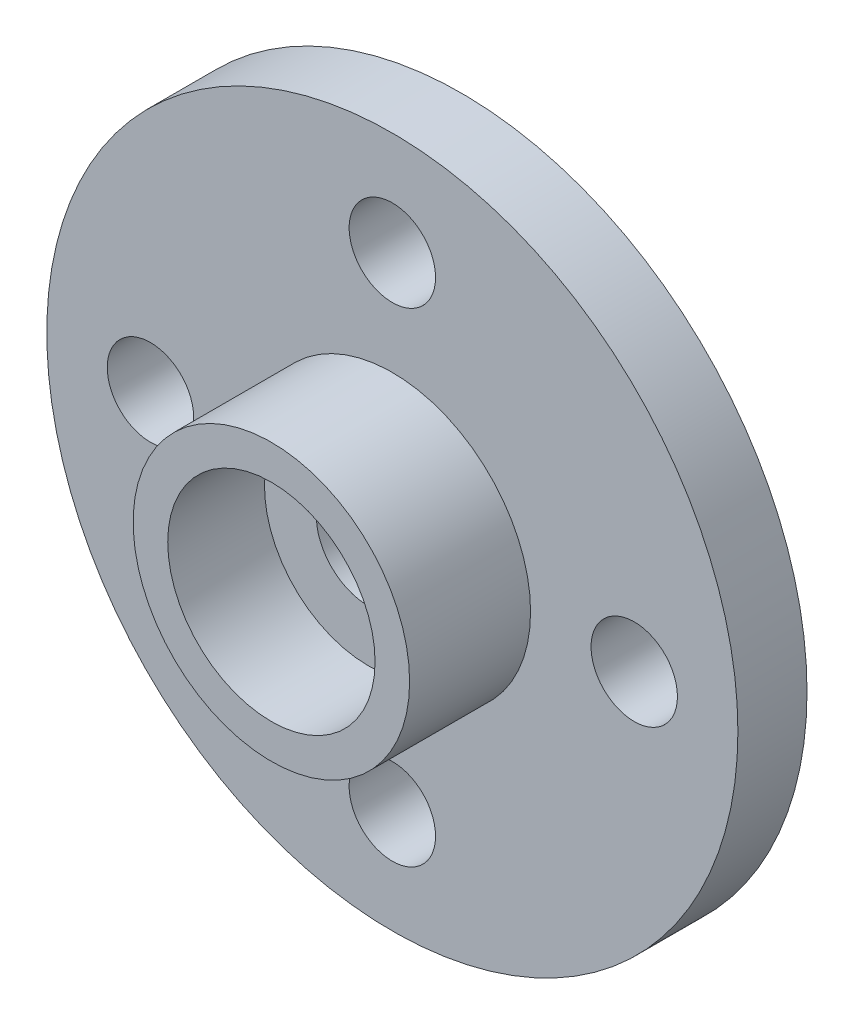
SolidWorks part; units mm, degrees
material "PF"
ref_plane "前视基准面" through (0, 0, 0) normal (0, 0, 1) x (1, 0, 0)
ref_plane "上视基准面" through (0, 0, 0) normal (0, 1, 0) x (1, 0, 0)
ref_plane "右视基准面" through (0, 0, 0) normal (1, 0, 0) x (0, 0, -1)
sketch "草图1" plane through (0, 0, 0) normal (0, 0, 1) x (1, 0, 0)
  circle A0 centre (0, 0) radius 3
  circle A1 centre (0, 0) radius 10
  dimension "D1" = 6
  dimension "D2" = 20
extrude "拉伸1" add sketch "草图1" along normal blind 2
sketch "草图2" plane through (0, 0, 2) normal (0, 0, 1) x (1, 0, 0)
  circle A0 centre (0, 0) radius 3
  circle A1 centre (0, 0) radius 4
extrude "凸台-拉伸1" add sketch "草图2" along normal blind 3.5
sketch "草图3" plane through (0, 0, 2) normal (0, 0, 1) x (1, 0, 0)
  circle A0 centre (0, 0) radius 7 construction
  point P2 (0, 7)
  point P3 (7, 0)
  point P4 (0, -7)
  point P5 (-7, 0)
  dimension "D1" = 14
hole_wizard "M3 螺纹孔1" positions "3D草图2" profile "草图5" tap size "M3" standard "GB" end condition through all
sketch3d "3D草图2"
  point P0 (-7, 0, 2)
  point P3 (0, 7, 2)
  point P6 (7, 0, 2)
  point P9 (0, -7, 2)
sketch "草图5" plane through (-7, 0, 2) normal (1, 0, 0) x (0, -1, 0)
  line L0 (0, 0) -> (0, 2)
  line L1 (0, 2) -> (1.25, 2)
  line L2 (1.25, 2) -> (1.25, 0)
  line L5 (1.25, 0) -> (0, 0)
  line L11 (0, -6.35) -> (0, 107.95) construction
  dimension "通孔螺纹孔钻头直径" = 2.5
  dimension "通孔螺纹孔钻头深度" = 2
cosmetic thread "孔螺蚊线1" parameters "D2"=3
cosmetic thread "孔螺蚊线2" parameters "D2"=3
cosmetic thread "孔螺蚊线3" parameters "D2"=3
cosmetic thread "孔螺蚊线4" parameters "D2"=3
sketch "草图6" plane through (0, 0, 0) normal (1, 0, 0) x (0, 0, -1)
  line L0 (0, 0) -> (-5.5, 0) construction
  line L2 (0, -10) -> (0, 10) construction
  line L3 (-1.4, 3) -> (-1.4, 1.5)
  line L4 (-1.4, 1.5) -> (-2.7, 1.5)
  line L5 (-2.7, 1.5) -> (-2.7, 3)
  line L6 (-2.7, 3) -> (-1.4, 3)
  line L7 (-5.5, 3) -> (-5.5, -3) construction
  dimension "D1" = 1.4
  dimension "D2" = 1.5
  dimension "D3" = 3
  dimension "D4" = 2.8
revolve "旋转1" add sketch "草图6" angle 360 about L0
sketch "草图7" plane through (0, 0, 1.4) normal (0, 0, -1) x (-1, 0, 0)
  circle A1 centre (0, 0) radius 3
  circle A2 centre (0, 0) radius 3
  dimension "D1" = 0
extrude "凸台-拉伸2" add sketch "草图7" along normal up to surface (1.4 mm away) up to face at (-5.75, 0, 0)
